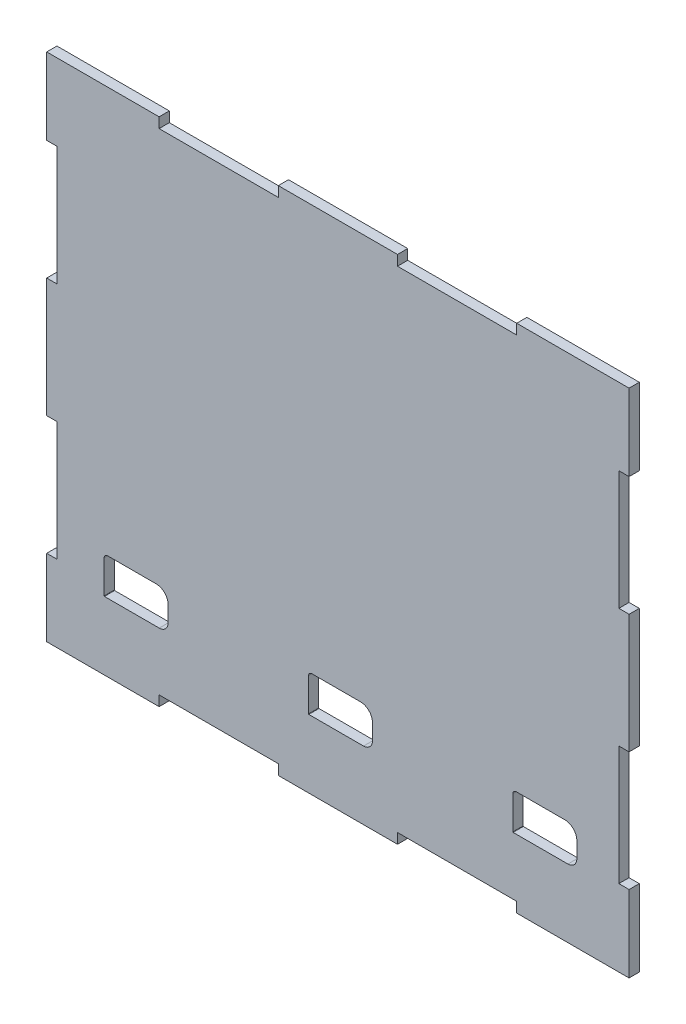
SolidWorks part; units mm, degrees
ref_plane "Front Plane" through (0, 0, 0) normal (0, 0, 1) x (1, 0, 0)
ref_plane "Top Plane" through (0, 0, 0) normal (0, 1, 0) x (1, 0, 0)
ref_plane "Right Plane" through (0, 0, 0) normal (1, 0, 0) x (0, 0, -1)
sketch "Model" plane through (0, 0, 0) normal (0, 0, 1) x (1, 0, 0)
  line L0 (85.5, 75) -> (82.5, 75)
  line L1 (82.5, 75) -> (52.5, 75)
  line L2 (52.5, 75) -> (52.5, 72)
  line L3 (52.5, 72) -> (17.5, 72)
  line L4 (17.5, 72) -> (17.5, 75)
  line L5 (17.5, 75) -> (-17.5, 75)
  line L6 (-17.5, 75) -> (-17.5, 72)
  line L7 (-17.5, 72) -> (-52.5, 72)
  line L8 (-52.5, 72) -> (-52.5, 75)
  line L9 (-52.5, 75) -> (-82.5, 75)
  line L10 (-82.5, 75) -> (-85.5, 75)
  line L11 (-85.5, 75) -> (-85.5, 72)
  line L12 (-85.5, 72) -> (-85.5, 52.5)
  line L13 (-85.5, 52.5) -> (-82.5, 52.5)
  line L14 (-82.5, 52.5) -> (-82.5, 17.5)
  line L15 (-82.5, 17.5) -> (-85.5, 17.5)
  line L16 (-85.5, 17.5) -> (-85.5, -17.5)
  line L17 (-85.5, -17.5) -> (-82.5, -17.5)
  line L18 (-82.5, -17.5) -> (-82.5, -52.5)
  line L19 (-82.5, -52.5) -> (-85.5, -52.5)
  line L20 (-85.5, -52.5) -> (-85.5, -72)
  line L21 (-85.5, -72) -> (-85.5, -75)
  line L22 (-85.5, -75) -> (-82.5, -75)
  line L23 (-82.5, -75) -> (-52.5, -75)
  line L24 (-52.5, -75) -> (-52.5, -72)
  line L25 (-52.5, -72) -> (-17.5, -72)
  line L26 (-17.5, -72) -> (-17.5, -75)
  line L27 (-17.5, -75) -> (17.5, -75)
  line L28 (17.5, -75) -> (17.5, -72)
  line L29 (17.5, -72) -> (52.5, -72)
  line L30 (52.5, -72) -> (52.5, -75)
  line L31 (52.5, -75) -> (82.5, -75)
  line L32 (82.5, -75) -> (85.5, -75)
  line L33 (85.5, -75) -> (85.5, -72)
  line L34 (85.5, -72) -> (85.5, -52.5)
  line L35 (85.5, -52.5) -> (82.5, -52.5)
  line L36 (82.5, -52.5) -> (82.5, -17.5)
  line L37 (82.5, -17.5) -> (85.5, -17.5)
  line L38 (85.5, -17.5) -> (85.5, 17.5)
  line L39 (85.5, 17.5) -> (82.5, 17.5)
  line L40 (82.5, 17.5) -> (82.5, 52.5)
  line L41 (82.5, 52.5) -> (85.5, 52.5)
  line L42 (85.5, 52.5) -> (85.5, 72)
  line L43 (85.5, 72) -> (85.5, 75)
extrude "Boss-Extrude1" add sketch "Model" along normal blind 3
sketch "Sketch2" plane through (0, 0, 3) normal (0, 0, 1) x (1, 0, 0)
  line L0 (-52.4625, -55) -> (-68.5375, -55)
  line L1 (-67.6375, -44.2) -> (-53.3625, -44.2)
  line L2 (-68.6375, -54.9) -> (-68.6375, -45.2)
  line L3 (-49.8375, -52.375) -> (-49.8375, -47.725)
  line L4 (-60.5, -55) -> (-60.5, -75) construction
  line L5 (7.5375, -55) -> (-8.5375, -55)
  line L6 (-7.6375, -44.2) -> (6.6375, -44.2)
  line L7 (-8.6375, -54.9) -> (-8.6375, -45.2)
  line L8 (10.1625, -52.375) -> (10.1625, -47.725)
  line L9 (67.5375, -55) -> (51.4625, -55)
  line L10 (52.3625, -44.2) -> (66.6375, -44.2)
  line L11 (51.3625, -54.9) -> (51.3625, -45.2)
  line L12 (70.1625, -52.375) -> (70.1625, -47.725)
  arc A0 (-49.8375, -52.375) -> (-52.4625, -55) centre (-52.4625, -52.375) cw
  arc A1 (-49.8375, -47.725) -> (-53.3625, -44.2) centre (-53.3625, -47.725) ccw
  arc A2 (-68.5375, -55) -> (-68.6375, -54.9) centre (-68.5375, -54.9) cw
  arc A3 (-68.6375, -45.2) -> (-67.6375, -44.2) centre (-67.6375, -45.2) cw
  arc A4 (10.1625, -52.375) -> (7.5375, -55) centre (7.5375, -52.375) cw
  arc A5 (10.1625, -47.725) -> (6.6375, -44.2) centre (6.6375, -47.725) ccw
  arc A6 (-8.5375, -55) -> (-8.6375, -54.9) centre (-8.5375, -54.9) cw
  arc A7 (-8.6375, -45.2) -> (-7.6375, -44.2) centre (-7.6375, -45.2) cw
  arc A8 (70.1625, -52.375) -> (67.5375, -55) centre (67.5375, -52.375) cw
  arc A9 (70.1625, -47.725) -> (66.6375, -44.2) centre (66.6375, -47.725) ccw
  arc A10 (51.4625, -55) -> (51.3625, -54.9) centre (51.4625, -54.9) cw
  arc A11 (51.3625, -45.2) -> (52.3625, -44.2) centre (52.3625, -45.2) cw
  dimension "D1" = 20
extrude "Cut-Extrude1" cut sketch "Sketch2" against normal through all
